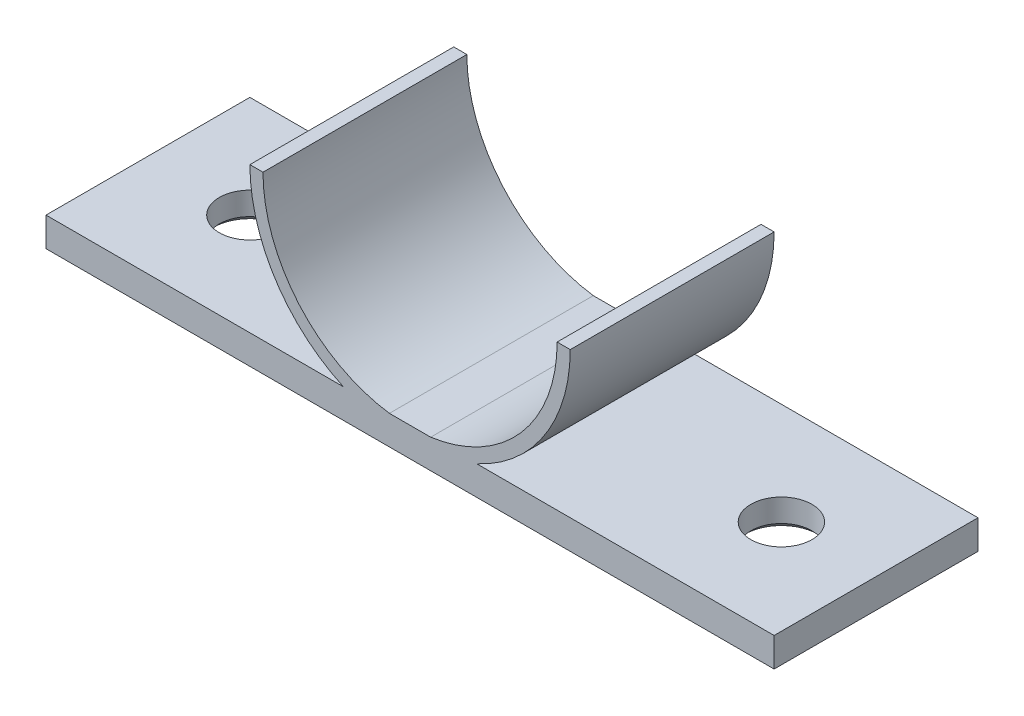
SolidWorks part; units mm, degrees
ref_plane "前视基准面" through (0, 0, 0) normal (0, 0, 1) x (1, 0, 0)
ref_plane "上视基准面" through (0, 0, 0) normal (0, 1, 0) x (1, 0, 0)
ref_plane "右视基准面" through (0, 0, 0) normal (1, 0, 0) x (0, 0, -1)
other "Configuration Table"
sketch "草图1" plane through (0, 0, 0) normal (0, 1, 0) x (1, 0, 0)
  line L0 (0, 14) -> (7, 14) construction
  line L1 (0, 0) -> (50, 0)
  line L2 (0, 0) -> (0, 14)
  line L3 (0, 14) -> (50, 14)
  line L4 (50, 0) -> (50, 14)
  line L5 (7, 14) -> (7, 7) construction
  line L6 (25, 14) -> (25, -0.2751) construction
  line L7 (7, 7) -> (43.5, 7) construction
  dimension "D1" = 50
  dimension "D2" = 14
  dimension "D3" = 7
  dimension "D4" = 7
extrude "凸台-拉伸1" add sketch "草图1" along normal blind 2
sketch "草图5" plane through (0, 0, 0) normal (0, 0, 1) x (1, 0, 0)
  line L1 (0, 2) -> (50, 2) construction
  line L2 (25, 2) -> (14.8, 2) construction
  line L4 (25, 12) -> (47.8118, 12) construction
  line L5 (14.8, 2) -> (23.5823, 2) construction
  line L7 (20.4174, 2) -> (23.5823, 2)
  line L8 (14, 12) -> (14.9, 12)
  line L9 (36, 12) -> (35.1, 12)
  line L10 (26.4177, 2) -> (34.8114, 2) construction
  line L11 (26.4177, 2) -> (29.5826, 2)
  arc A3 (14.9, 12) -> (23.5823, 2) centre (25, 12) ccw
  arc A4 (14, 12) -> (20.4174, 2) centre (25, 12) ccw
  arc A5 (29.5826, 2) -> (36, 12) centre (25, 12) ccw
  arc A6 (26.4177, 2) -> (35.1, 12) centre (25, 12) ccw
  dimension "D1" = 10.2
  dimension "D2" = 10
extrude "凸台-拉伸2" add sketch "草图5" against normal blind 14
sketch "草图6" plane through (0, 0, 0) normal (0, -1, 0) x (1, 0, 0)
  line L0 (7, -7) -> (43.5, -7) construction
  circle A0 centre (7, -7) radius 2.25
  circle A1 centre (43.5, -7) radius 2.25
  point P1 (7, -7)
  point P7 (43.5, -7)
  point P15 (7, -7)
  point P17 (43.5, -7)
hole_wizard "M5 螺纹孔3" positions "草图6" profile "草图7" tap size "M5" standard "GB"
sketch "草图7" plane through (43.5, 0, -7) normal (1, 0, 0) x (0, 0, -1)
  line L0 (0, 0) -> (0, 13.6618)
  line L1 (0, 13.6618) -> (2.1, 12.4)
  line L2 (2.1, 12.4) -> (2.1, 0.425)
  line L3 (2.1, 0.425) -> (2.525, 0)
  line L5 (2.525, 0) -> (0, 0)
  line L6 (-2.1, 0.425) -> (-2.525, 0) construction
  line L10 (0, 13.6618) -> (-2.1, 12.4) construction
  line L11 (0, -6.35) -> (0, 107.95) construction
  dimension "螺纹孔钻头直径" = 4.2
  dimension "螺纹孔钻头深度" = 12.4
  dimension "近端锥形沉头孔直径" = 5.05
  dimension "近端锥形沉头孔角度" = 90
  dimension "导头角度" = 118
cosmetic thread "孔螺蚊线3" parameters "D1"=10, "D2"=5
cosmetic thread "孔螺蚊线4" parameters "D1"=10, "D2"=5
